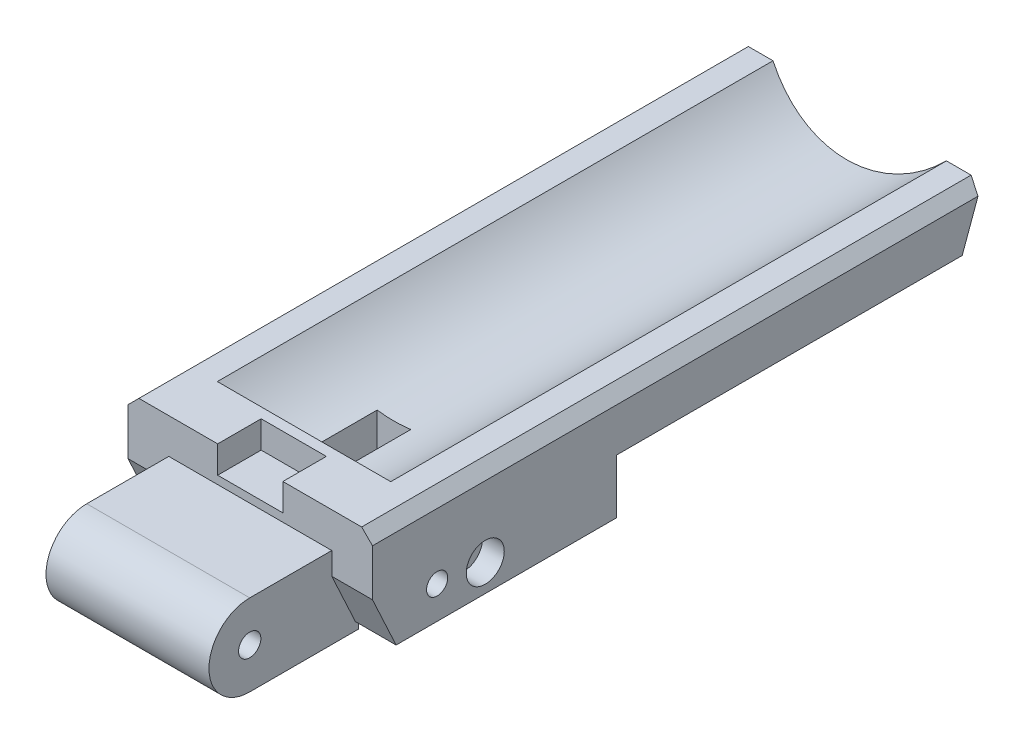
SolidWorks part; units mm, degrees
ref_plane "정면" through (0, 0, 0) normal (0, 0, 1) x (1, 0, 0)
ref_plane "윗면" through (0, 0, 0) normal (0, 1, 0) x (1, 0, 0)
ref_plane "우측면" through (0, 0, 0) normal (1, 0, 0) x (0, 0, -1)
sketch "스케치1" plane through (0, 0, 0) normal (1, 0, 0) x (0, 0, -1)
  line L0 (0, -7.5) -> (37.9385, -7.5)
  line L1 (37.9385, -7.5) -> (36.6134, 7.5)
  line L2 (36.6134, 7.5) -> (0, 7.5)
  line L3 (0, 7.5) -> (0, 0) construction
  line L4 (0, 0) -> (0, -7.5) construction
  circle A0 centre (0, 0) radius 2.05
  circle A1 centre (0, 0) radius 7.5
  dimension "D1" = 4.1
  dimension "D2" = 15
extrude "보스-돌출1" add sketch "스케치1" along normal mid plane 30 contours A1 L0 L1 L2 | A1 A0
sketch "스케치2" plane through (0, 0, 0) normal (1, 0, 0) x (0, 0, -1)
  line L0 (0, 0) -> (15.1, 0) construction
  line L1 (15.1, 3.3892) -> (15.1, 14)
  line L3 (15.1, 14) -> (127.2794, 14)
  line L5 (19.4476, -6) -> (120, -6)
  line L6 (120, -6) -> (127.2794, 14)
  line L7 (19.4476, -6) -> (15.1, 3.3892)
  dimension "D1" = 14
  dimension "D2" = 15.1
  dimension "D3" = 120
  dimension "D4" = 70
  dimension "D5" = 6
extrude "보스-돌출2" add sketch "스케치2" along normal mid plane 45
ref_plane "평면1" through (0, 0, -150) normal (0, 0, 1) x (1, 0, 0)
sketch "스케치3" plane through (0, 0, -150) normal (0, 0, 1) x (1, 0, 0)
  line L0 (0, 0) -> (0, 30) construction
  circle A0 centre (0, 30) radius 22.6
  dimension "D1" = 45.2
  dimension "D2" = 30
extrude "컷-돌출1" cut sketch "스케치3" along normal blind 125
sketch "스케치5" plane through (22.5, 0, 0) normal (1, 0, 0) x (0, 0, -1)
  line L1 (60, 4) -> (140, 4)
  line L2 (60, 4) -> (60, -11)
  line L3 (60, -11) -> (140, -11)
  line L4 (140, 4) -> (140, -11)
  dimension "D1" = 15
  dimension "D2" = 80
  dimension "D3" = 60
  dimension "D4" = 4
extrude "컷-돌출2" cut sketch "스케치5" against normal blind 15
mirror "대칭 복사1" about plane through (0, 0, 0) normal (1, 0, 0) of "컷-돌출2"
sketch "스케치6" plane through (0, 0, 0) normal (1, 0, 0) x (0, 0, -1)
  line L0 (70, -1) -> (110, -1) construction
  line L1 (70, -1) -> (0, -1) construction
  line L2 (0, -1) -> (0, 0) construction
  circle A0 centre (70, -1) radius 1.95
  circle A1 centre (110, -1) radius 1.95
  dimension "D1" = 3.9
  dimension "D2" = 3.9
  dimension "D3" = 40
  dimension "D4" = 1
  dimension "D5" = 70
extrude "컷-돌출3" cut sketch "스케치6" against normal through all both and the other way through all
sketch "스케치10" plane through (0, 0, 0) normal (1, 0, 0) x (0, 0, -1)
  line L0 (0, 0) -> (27, 0) construction
  circle A0 centre (27, 0) radius 1.95
  dimension "D1" = 3.9
  dimension "D2" = 27
extrude "컷-돌출4" cut sketch "스케치10" against normal through all both and the other way through all
sketch "스케치11" plane through (0, 0, 0) normal (1, 0, 0) x (0, 0, -1)
  circle A0 centre (35.8504, -1) radius 2.05
  dimension "D1" = 4.1
  dimension "D2" = 1
extrude "컷-돌출5" cut sketch "스케치11" against normal through all both and the other way through all
sketch "스케치12" plane through (0, 0, 0) normal (1, 0, 0) x (0, 0, -1)
  line L0 (35.8504, -1) -> (35.8504, 12.9437) construction
  line L1 (30.1504, -1) -> (30.1504, 12.9437)
  line L2 (41.5504, -1) -> (41.5504, 12.9437)
  arc A0 (30.1504, -1) -> (41.5504, -1) centre (35.8504, -1) ccw
  arc A1 (41.5504, 12.9437) -> (30.1504, 12.9437) centre (35.8504, 12.9437) ccw
  point P3 (35.8504, 5.9718)
  dimension "D1" = 5.7
extrude "컷-돌출6" cut sketch "스케치12" against normal mid plane 6.2
ref_plane "평면2" through (0, 0, -30) normal (0, 0, 1) x (1, 0, 0)
sketch "스케치16" plane through (0, 0, 0) normal (1, 0, 0) x (0, 0, -1)
  line L0 (35.8504, -1) -> (35.8504, -5) construction
  line L1 (20, -5) -> (120, -5)
  line L2 (20, -5) -> (20, -20.085)
  line L3 (20, -20.085) -> (120, -20.085)
  line L4 (120, -5) -> (120, -20.085)
  line L5 (0, 0) -> (20, 0) construction
  line L6 (20, 0) -> (20, -5) construction
  dimension "D1" = 4
  dimension "D2" = 100
  dimension "D3" = 20
extrude "컷-돌출7" cut sketch "스케치16" against normal mid plane 10
chamfer "모따기1" distance 2 angle 45 2 edges at (-22.5, 14, -71.1897) (22.5, 14, -71.1897)
sketch "스케치17" plane through (22.5, 0, 0) normal (1, 0, 0) x (0, 0, -1)
  circle A1 centre (35.8504, -1) radius 3.5
  dimension "D2" = 7
extrude "컷-돌출8" cut sketch "스케치17" against normal blind 4
sketch "스케치19" plane through (0, 14, 0) normal (0, 1, 0) x (1, 0, 0)
  line L0 (0, -11.825) -> (0, 11.825) construction
  line L1 (-6, 23.1) -> (6, 23.1)
  line L2 (-6, 23.1) -> (-6, 15.1)
  line L3 (-6, 15.1) -> (6, 15.1)
  line L4 (6, 23.1) -> (6, 15.1)
  line L5 (-6, 23.1) -> (6, 15.1) construction
  line L6 (-6, 15.1) -> (6, 23.1) construction
  line L7 (20.5, 15.1) -> (-20.5, 15.1) construction
  point P0 (0, 19.1)
  dimension "D1" = 12
  dimension "D2" = 8
extrude "컷-돌출10" cut sketch "스케치19" against normal blind 5
sketch "스케치20" plane through (0, -6, 0) normal (0, -1, 0) x (1, 0, 0)
  line L0 (15, -37.806) -> (15, -19.4476) construction
  line L1 (-15, -38.1966) -> (15, -38.1966)
  line L2 (-15, -38.1966) -> (-15, -20)
  line L3 (-15, -20) -> (15, -20)
  line L4 (15, -38.1966) -> (15, -20)
  line L5 (-5, -20) -> (5, -20) construction
extrude "컷-돌출12" cut sketch "스케치20" along normal up to next
sketch "스케치21" plane through (0, -6, 0) normal (0, -1, 0) x (1, 0, 0)
  line L0 (12, -42) -> (12, -67) construction
  line L1 (12, -42) -> (12, -20) construction
  line L2 (-15, -20) -> (15, -20) construction
  line L3 (0, 0) -> (0, -143.349) construction
  line L4 (0, -11.825) -> (0, 11.825) construction
  circle A0 centre (12, -42) radius 1.925
  circle A1 centre (-12, -42) radius 1.925
  dimension "D3" = 3.85
  dimension "D1" = 22
  dimension "D2" = 25
  dimension "D4" = 12
extrude "컷-돌출13" cut sketch "스케치21" against normal blind 5
